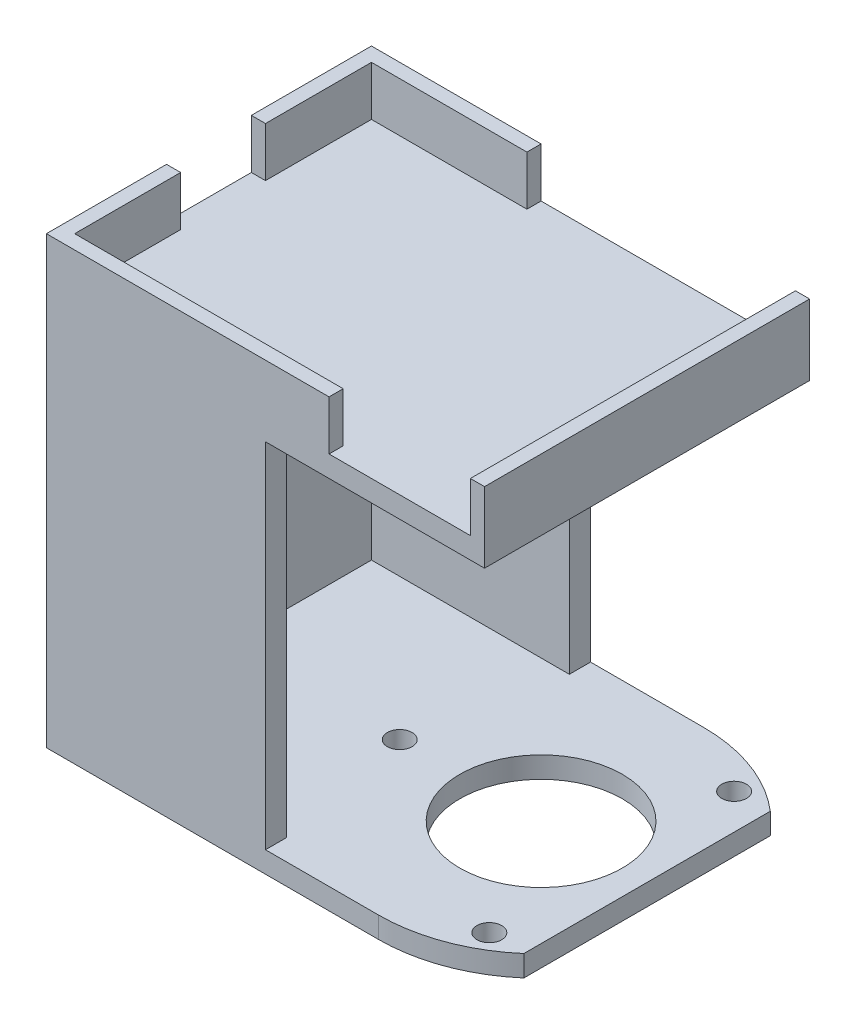
SolidWorks part; units mm, degrees
material "ABS"
ref_plane "前视基准面" through (0, 0, 0) normal (0, 0, 1) x (1, 0, 0)
ref_plane "上视基准面" through (0, 0, 0) normal (0, 1, 0) x (1, 0, 0)
ref_plane "右视基准面" through (0, 0, 0) normal (1, 0, 0) x (0, 0, -1)
sketch "草图1" plane through (0, 0, 0) normal (0, 1, 0) x (1, 0, 0)
  line L1 (-31, 23) -> (31, 23)
  line L2 (-31, 23) -> (-31, -23)
  line L3 (-31, -23) -> (31, -23)
  line L4 (31, 23) -> (31, -23)
  line L5 (-31, 23) -> (31, -23) construction
  line L6 (-31, -23) -> (31, 23) construction
  point P0 (0, 0)
  dimension "D1" = 62
  dimension "D2" = 46
extrude "凸台-拉伸1" add sketch "草图1" along normal blind 10
sketch "草图2" plane through (0, 10, 0) normal (0, 1, 0) x (1, 0, 0)
  line L1 (-29, 21) -> (29, 21)
  line L2 (-29, 21) -> (-29, -21)
  line L3 (-29, -21) -> (29, -21)
  line L4 (29, 21) -> (29, -21)
  line L5 (-29, 21) -> (29, -21) construction
  line L6 (-29, -21) -> (29, 21) construction
  point P0 (0, 0)
  dimension "D1" = 58
  dimension "D2" = 42
extrude "切除-拉伸1" cut sketch "草图2" against normal blind 7
sketch "草图3" plane through (-31, 0, 0) normal (-1, 0, 0) x (0, 0, 1)
  line L0 (-6, 17) -> (-6, 3)
  line L1 (-6, 17) -> (6, 17)
  line L2 (-6, 3) -> (6, 3)
  line L3 (6, 17) -> (6, 3)
  line L4 (-6, 17) -> (6, 3) construction
  line L5 (-6, 3) -> (6, 17) construction
  line L6 (-23, 10) -> (23, 10) construction
  point P0 (0, 10)
  point P1 (0, 10)
  point P2 (0, 0)
  point P5 (0, 0)
  dimension "D1" = 14
  dimension "D2" = 12
extrude "切除-拉伸2" cut sketch "草图3" against normal up to next
sketch "草图5" plane through (0, 0, -21) normal (0, 0, 1) x (1, 0, 0)
  line L0 (29, 3) -> (-29, 3) construction
  line L1 (29, 10) -> (-7, 10)
  line L2 (29, 10) -> (29, 3)
  line L3 (29, 3) -> (-7, 3)
  line L4 (-7, 10) -> (-7, 3)
  dimension "D1" = 36
extrude "切除-拉伸3" cut sketch "草图5" against normal up to next
sketch "草图6" plane through (0, 0, 21) normal (0, 0, -1) x (-1, 0, 0)
  line L0 (29, 3) -> (-29, 3) construction
  line L1 (-29, 10) -> (-9, 10)
  line L2 (-29, 10) -> (-29, 3)
  line L3 (-29, 3) -> (-9, 3)
  line L4 (-9, 10) -> (-9, 3)
  dimension "D1" = 20
extrude "切除-拉伸4" cut sketch "草图6" against normal up to next
sketch "草图8" plane through (0, 0, 0) normal (0, -1, 0) x (1, 0, 0)
  line L0 (-31, 23) -> (31, 23) construction
  line L1 (28, -20) -> (-28, -20)
  line L2 (28, -20) -> (28, 20)
  line L3 (28, 20) -> (-28, 20)
  line L4 (-28, -20) -> (-28, 20)
  line L5 (28, -20) -> (-28, 20) construction
  line L6 (28, 20) -> (-28, -20) construction
  line L7 (-31, -23) -> (-31, 23) construction
  line L10 (0, 23) -> (-31, 23)
  line L11 (0, 23) -> (0, -23)
  line L12 (0, -23) -> (-31, -23)
  line L13 (-31, 23) -> (-31, -23)
  point P0 (0, 0)
  line M4 (31, 23) -> (-31, 23)
  line M5 (-31, 23) -> (-31, -23)
  line M6 (-31, -23) -> (31, -23)
  dimension "D1" = 3
  dimension "D2" = 3
extrude "凸台-拉伸2" add sketch "草图8" along normal blind 50 contours L11 L1 L4 L3 M4 M5 M6
sketch "草图9" plane through (0, -50, 0) normal (0, -1, 0) x (1, 0, 0)
  line L1 (31, -23) -> (-31, -23)
  line L2 (31, -23) -> (31, 23)
  line L3 (31, 23) -> (-31, 23)
  line L4 (-31, -23) -> (-31, 23)
  line L5 (31, -23) -> (-31, 23) construction
  line L6 (31, 23) -> (-31, -23) construction
  point P0 (0, 0)
extrude "凸台-拉伸3" add sketch "草图9" along normal blind 3
sketch "草图10" plane through (0, -53, 0) normal (0, -1, 0) x (1, 0, 0)
  line L0 (0, 0) -> (31, 0) construction
  line L1 (31, -23) -> (31, 23) construction
  line L2 (16, 0) -> (26, 17.3205) construction
  line L3 (16, 0) -> (26, -17.3205) construction
  line L4 (-31, -23) -> (31, -23) construction
  line L6 (31, 23) -> (16, 23)
  line L7 (31, 23) -> (31, -23)
  line L8 (31, -23) -> (16, -23)
  line L9 (16, 23) -> (16, -23)
  circle A0 centre (16, 0) radius 11.5
  circle A1 centre (16, 0) radius 20 construction
  circle A2 centre (26, 17.3205) radius 1.75
  circle A3 centre (26, -17.3205) radius 1.75
  circle A4 centre (-4, 0) radius 1.75
  circle A5 centre (16, 0) radius 23
  line M5 (-31, -23) -> (31, -23)
  line M6 (31, -23) -> (31, 23)
  line M7 (31, 23) -> (-31, 23)
  dimension "D1" = 23
  dimension "D2" = 40
  dimension "D6" = 3.5
  dimension "D3" = 60
  dimension "D4" = 60
  dimension "D5" = 5
extrude "切除-拉伸5" cut sketch "草图10" against normal up to next contours A5 M6 M7 | A5 M5 M6 | A3 | A2 | L9 A0 | L9 A0 | A4
